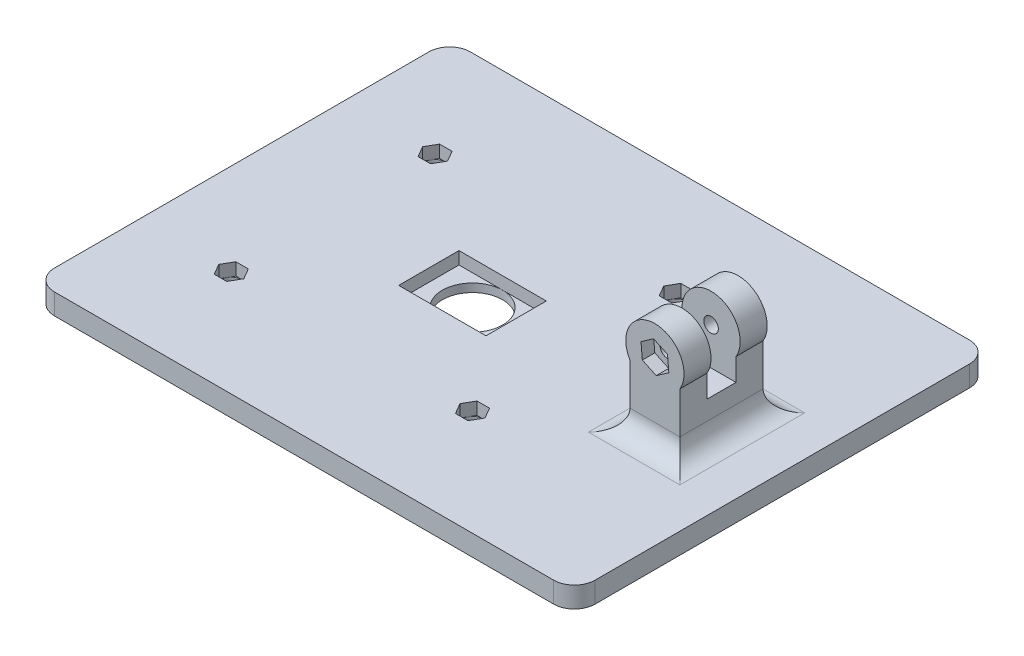
SolidWorks part; units mm, degrees
ref_plane "Front" through (0, 0, 0) normal (0, 0, 1) x (1, 0, 0)
ref_plane "Top" through (0, 0, 0) normal (0, 1, 0) x (1, 0, 0)
ref_plane "Right" through (0, 0, 0) normal (1, 0, 0) x (0, 0, -1)
sketch "Esquisse1" plane through (0, 0, 0) normal (0, 1, 0) x (1, 0, 0)
  line L1 (-52.4815, 50.6056) -> (77.5185, 50.6056)
  line L2 (-52.4815, 50.6056) -> (-52.4815, -49.3944)
  line L3 (-52.4815, -49.3944) -> (77.5185, -49.3944)
  line L4 (77.5185, 50.6056) -> (77.5185, -49.3944)
extrude "Boss.-Extru.1" add sketch "Esquisse1" along normal blind 5
sketch "Esquisse5" plane through (0, 5, 0) normal (0, 1, 0) x (1, 0, 0)
  line L2 (-52.4815, 50.6056) -> (-52.4815, -49.3944) construction
  line L3 (-28.9745, 22.5116) -> (-27.4815, 25.1137)
  line L4 (-27.4815, 25.1137) -> (-28.9885, 27.7077)
  line L5 (-28.9885, 27.7077) -> (-31.9885, 27.6997)
  line L6 (-31.9885, 27.6997) -> (-33.4815, 25.0975)
  line L7 (-33.4815, 25.0975) -> (-31.9745, 22.5035)
  line L8 (-31.9745, 22.5035) -> (-28.9745, 22.5116)
  line L9 (77.5185, 50.6056) -> (-52.4815, 50.6056) construction
  circle A1 centre (-30.4815, 25.1056) radius 3 construction
  dimension "D1" = 22
  dimension "D2" = 25.5
extrude "Enlèv. mat.-Extru.3" cut sketch "Esquisse5" against normal blind 3
pattern_linear "Répétition linéaire1" count 2 spacing 58 along (1, 0, 0) count 2 spacing 49 along (0, 0, 1) of "Enlèv. mat.-Extru.3"
sketch "Esquisse8" plane through (0, 5, 0) normal (0, 1, 0) x (1, 0, 0)
  circle A0 centre (-30.4815, 25.1056) radius 2.5981
extrude "Enlèv. mat.-Extru.4" cut sketch "Esquisse8" against normal through all
pattern_linear "Répétition linéaire2" count 2 spacing 58 along (1, 0, 0) count 2 spacing 49 along (0, 0, 1) of "Enlèv. mat.-Extru.4"
sketch "Esquisse9" plane through (0, 5, 0) normal (0, 1, 0) x (1, 0, 0)
  line L1 (50.8849, 10.6056) -> (62.8849, 10.6056)
  line L2 (50.8849, 10.6056) -> (50.8849, -9.3944)
  line L3 (50.8849, -9.3944) -> (62.8849, -9.3944)
  line L4 (62.8849, 10.6056) -> (62.8849, -9.3944)
  line L5 (77.5185, 50.6056) -> (-52.4815, 50.6056) construction
  dimension "D1" = 20
  dimension "D2" = 12
  dimension "D3" = 40
extrude "Boss.-Extru.2" add sketch "Esquisse9" along normal blind 15
sketch "Esquisse10" plane through (0, 0, 9.3944) normal (0, 0, 1) x (1, 0, 0)
  line L0 (50.8849, 20) -> (62.8849, 20)
  arc A0 (50.8849, 20) -> (62.8849, 20) centre (56.8849, 23.6056) cw
extrude "Boss.-Extru.3" add sketch "Esquisse10" against normal blind 20
ref_plane "Plan3" through (0, 30.6056, 0) normal (0, 1, 0) x (1, 0, 0)
sketch "Esquisse14" plane through (0, 30.6056, 0) normal (0, 1, 0) x (1, 0, 0)
  line L0 (77.5185, -49.3944) -> (77.5185, 50.6056) construction
  line L1 (49.0185, 4.1056) -> (65.0185, 4.1056)
  line L2 (49.0185, 4.1056) -> (49.0185, -2.8944)
  line L3 (49.0185, -2.8944) -> (65.0185, -2.8944)
  line L4 (65.0185, 4.1056) -> (65.0185, -2.8944)
  line L6 (63.8849, 10.6056) -> (49.8849, 10.6056) construction
  dimension "D1" = 7
  dimension "D2" = 16
  dimension "D3" = 12.5
  dimension "D4" = 6.5
extrude "Enlèv. mat.-Extru.6" cut sketch "Esquisse14" against normal blind 16
ref_plane "Plan4" through (0, 0, 19.3944) normal (0, 0, 1) x (1, 0, 0)
sketch "Esquisse17" plane through (0, 0, 19.3944) normal (0, 0, 1) x (1, 0, 0)
  line L7 (60.2313, 22.0388) -> (59.9149, 25.7203)
  line L8 (59.9149, 25.7203) -> (56.5685, 27.287)
  line L9 (56.5685, 27.287) -> (53.5384, 25.1723)
  line L10 (53.5384, 25.1723) -> (53.8548, 21.4908)
  line L11 (53.8548, 21.4908) -> (57.2013, 19.9241)
  line L12 (57.2013, 19.9241) -> (60.2313, 22.0388)
  circle A1 centre (56.8849, 23.6056) radius 7
  circle A2 centre (56.8849, 23.6056) radius 3.2 construction
extrude "Enlèv. mat.-Extru.7" cut sketch "Esquisse17" against normal blind 13 contours L7 L8 L9 L10 L11 L12
sketch "Esquisse18" plane through (0, 0, 19.3944) normal (0, 0, 1) x (1, 0, 0)
  circle A1 centre (56.8849, 23.6056) radius 1.75
extrude "Enlèv. mat.-Extru.8" cut sketch "Esquisse18" against normal blind 33
fillet "Congé1" radius 5 4 edges at (50.8849, 5, -0.6056) (56.8849, 5, -10.6056) (62.8849, 5, -0.6056) (56.8849, 5, 9.3944)
fillet "Congé2" radius 5 4 edges at (-52.4815, 2.5, -50.6056) (-52.4815, 2.5, 49.3944) (77.5185, 2.5, 49.3944) (77.5185, 2.5, -50.6056)
sketch "Esquisse19" plane through (0, 5, 0) normal (0, 1, 0) x (1, 0, 0)
  line L0 (72.5185, 50.6056) -> (-47.4815, 50.6056) construction
  line L1 (-7.4815, 7.8556) -> (13.5185, 7.8556)
  line L2 (-7.4815, 7.8556) -> (-7.4815, -6.6444)
  line L3 (-7.4815, -6.6444) -> (13.5185, -6.6444)
  line L4 (13.5185, 7.8556) -> (13.5185, -6.6444)
  line L5 (-52.4815, 45.6056) -> (-52.4815, -44.3944) construction
  dimension "D1" = 14.5
  dimension "D2" = 21
  dimension "D3" = 42.75
  dimension "D4" = 45
extrude "Enlèv. mat.-Extru.9" cut sketch "Esquisse19" against normal blind 3
sketch "Esquisse20" plane through (0, 5, 0) normal (0, 1, 0) x (1, 0, 0)
  line L0 (-7.4815, 7.8556) -> (-7.4815, -6.6444) construction
  circle A0 centre (3.0185, 0.6056) radius 7.25
  dimension "D1" = 10.5
extrude "Enlèv. mat.-Extru.10" cut sketch "Esquisse20" against normal blind 12
